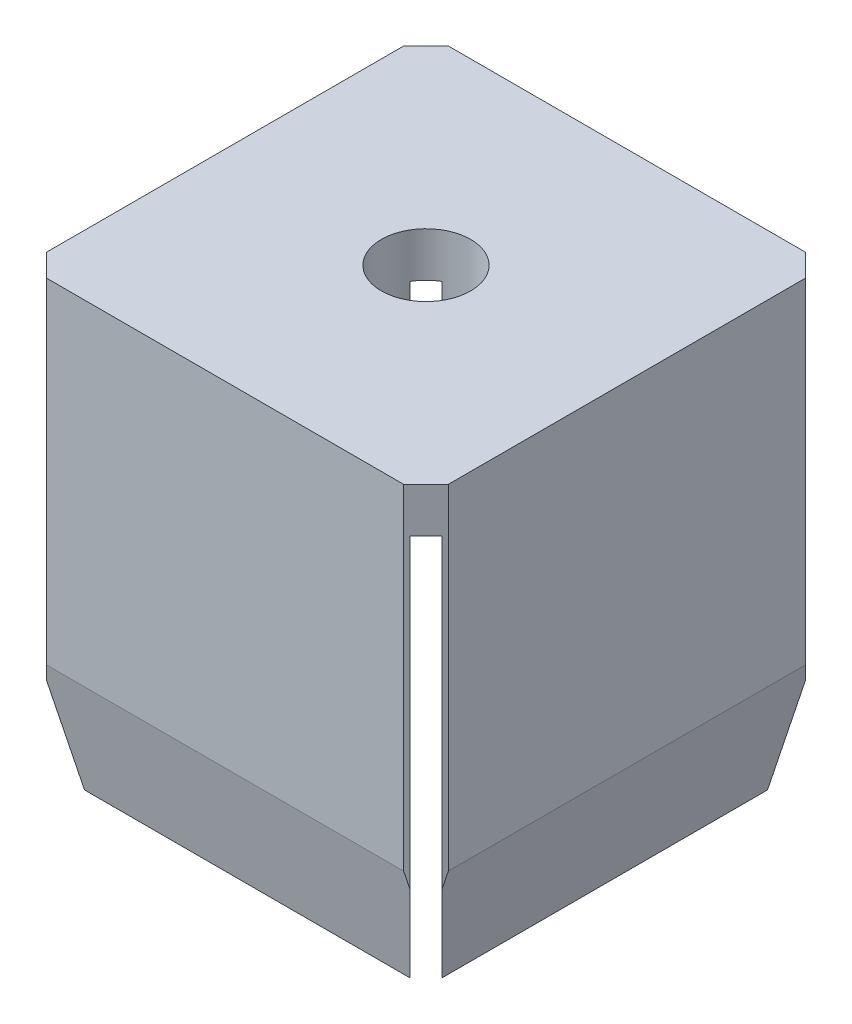
SolidWorks part; units mm, degrees
ref_plane "Front Plane" through (0, 0, 0) normal (0, 0, 1) x (1, 0, 0)
ref_plane "Top Plane" through (0, 0, 0) normal (0, 1, 0) x (1, 0, 0)
ref_plane "Right Plane" through (0, 0, 0) normal (1, 0, 0) x (0, 0, -1)
sketch "Sketch1" plane through (0, 0, 0) normal (0, 1, 0) x (1, 0, 0)
  line L1 (-18, -18) -> (18, -18)
  line L2 (-18, -18) -> (-18, 18)
  line L3 (-18, 18) -> (18, 18)
  line L4 (18, -18) -> (18, 18)
  line L5 (-18, -18) -> (18, 18) construction
  line L6 (-18, 18) -> (18, -18) construction
  circle A0 centre (0, 0) radius 4
  point P0 (0, 0)
  dimension "D2" = 8
  dimension "D1" = 36
extrude "Boss-Extrude1" add sketch "Sketch1" along normal blind 40
sketch "Sketch2" plane through (0, 0, 0) normal (0, 1, 0) x (1, 0, 0)
  line L0 (-18.5858, -20) -> (0, -1.4142)
  line L1 (-20, 20) -> (-18.5858, 20)
  line L2 (-20, 20) -> (-20, 18.5858)
  line L3 (-20, -20) -> (-18.5858, -20)
  line L4 (20, 20) -> (20, 18.5858)
  line L5 (-20, 20) -> (20, -20) construction
  line L6 (-20, -20) -> (20, 20) construction
  line L7 (-20, 18.5858) -> (-1.4142, 0)
  line L8 (-20, -18.5858) -> (-1.4142, 0)
  line L9 (-18.5858, 20) -> (0, 1.4142)
  line L10 (1.4142, 0) -> (20, -18.5858)
  line L11 (-19.2929, 20.7071) -> (20.7071, -19.2929) construction
  line L12 (0, 1.4142) -> (18.5858, 20)
  line L13 (-20.7071, -19.2929) -> (19.2929, 20.7071) construction
  line L14 (0, -1.4142) -> (18.5858, -20)
  line L15 (-20.7071, 19.2929) -> (19.2929, -20.7071) construction
  line L16 (1.4142, 0) -> (20, 18.5858)
  line L17 (-19.2929, -20.7071) -> (20.7071, 19.2929) construction
  line L18 (-20, -18.5858) -> (-20, -20)
  line L19 (18.5858, -20) -> (20, -20)
  line L20 (20, -18.5858) -> (20, -20)
  line L21 (18.5858, 20) -> (20, 20)
  point P0 (0, 0)
  dimension "D1" = 40
  dimension "D2" = 1
  dimension "D3" = 1
extrude "Cut-Extrude1" cut sketch "Sketch2" along normal blind 36
chamfer "Chamfer1" distance 2 angle 45 4 edges at (-18, 38, -18) (18, 38, -18) (-18, 38, 18) (18, 38, 18)
chamfer "Chamfer2" distance 2 distance2 10 4 edges at (0, 0, -18) (18, 0, 0) (0, 0, 18) (-18, 0, 0)
